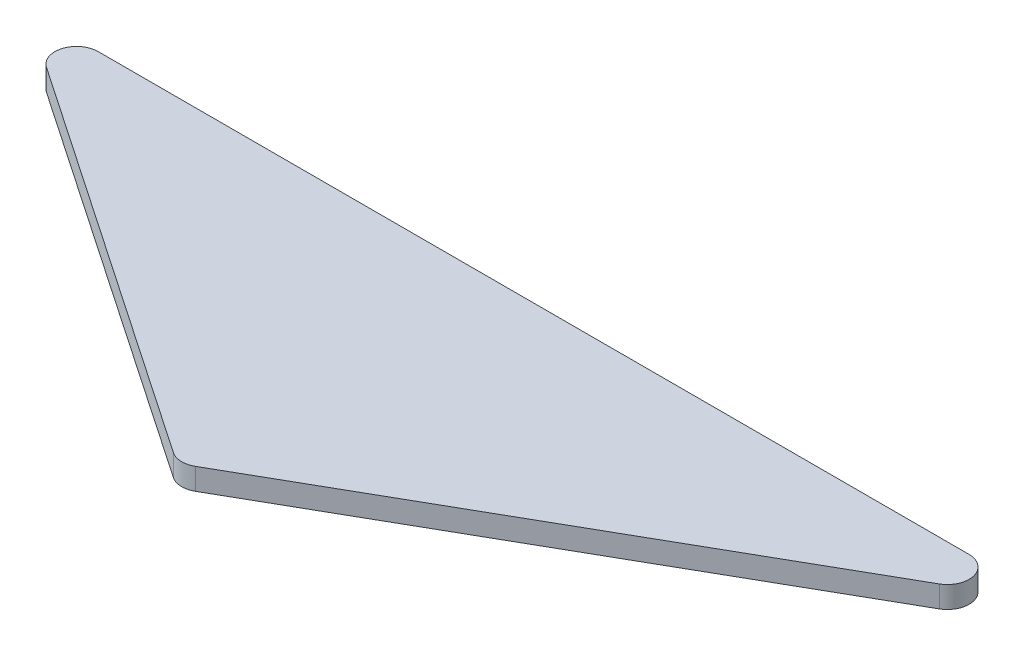
SolidWorks part; units mm, degrees
ref_plane "Front Plane" through (0, 0, 0) normal (0, 0, 1) x (1, 0, 0)
ref_plane "Top Plane" through (0, 0, 0) normal (0, 1, 0) x (1, 0, 0)
ref_plane "Right Plane" through (0, 0, 0) normal (1, 0, 0) x (0, 0, -1)
sketch "Sketch1" plane through (0, 0, 0) normal (0, 1, 0) x (1, 0, 0)
  line L0 (0, 0) -> (-68.3866, 46.5299)
  line L1 (0, 0) -> (81.6134, 46.5299)
  line L2 (81.6134, 46.5299) -> (-68.3866, 46.5299)
  point P4 (67.6922, 44.6954)
  point P7 (-75.8888, 43.0743)
  point P9 (38.976, 42.2638)
  point P10 (-77.0467, 48.1691)
  point P11 (0, 0)
  point P12 (-68.3866, 46.5299)
  point P13 (0, 0)
  point P14 (0, 0)
  dimension "D1" = 150
  dimension "D2" = 82.7149
  dimension "D3" = 93.9456
extrude "Boss-Extrude1" add sketch "Sketch1" along normal blind 3.175
fillet "Fillet1" radius 3.175 3 edges at (-68.3866, 1.5875, -46.5299) (81.6134, 1.5875, -46.5299) (0, 1.5875, 0)
sketch "Sketch2" plane through (0, 3.175, 0) normal (0, 1, 0) x (1, 0, 0)
  circle A4 centre (-58.0761, 43.3549) radius 0.7129
  arc A5 (-58.0761, 46.5299) -> (-59.8621, 40.7299) centre (-58.0761, 43.3549) ccw construction
extrude "Boss-Extrude2" add sketch "Sketch2" against normal blind 2.54
